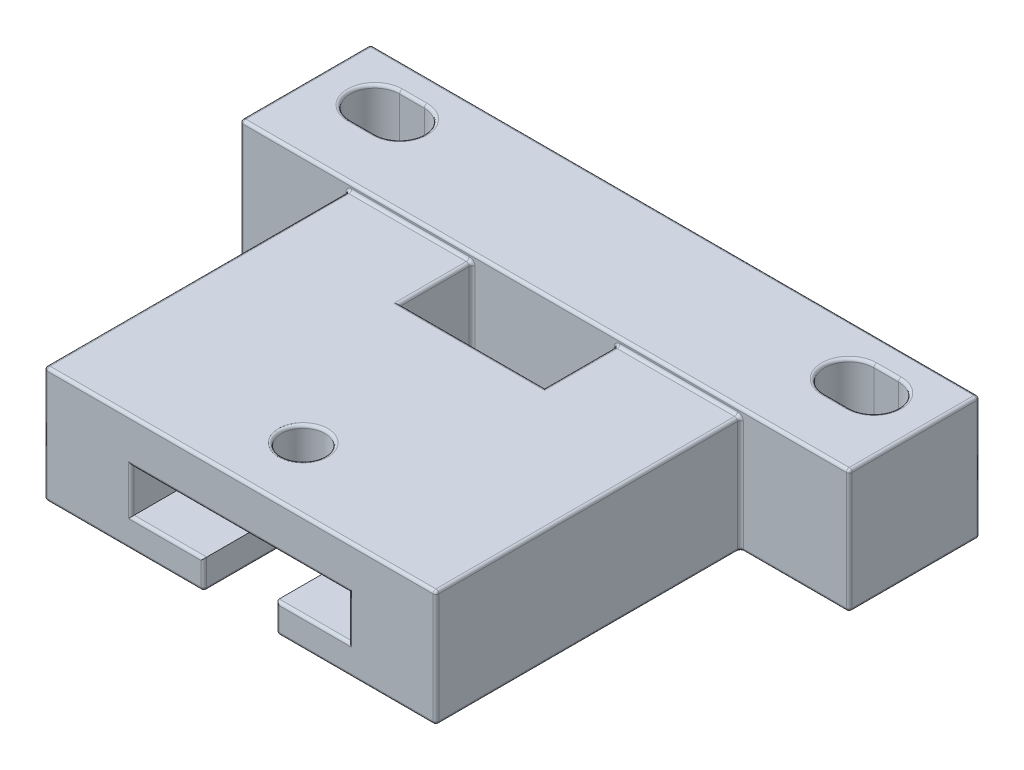
SolidWorks part; units mm, degrees
ref_plane "Front Plane" through (0, 0, 0) normal (0, 0, 1) x (1, 0, 0)
ref_plane "Top Plane" through (0, 0, 0) normal (0, 1, 0) x (1, 0, 0)
ref_plane "Right Plane" through (0, 0, 0) normal (1, 0, 0) x (0, 0, -1)
sketch "Sketch2" plane through (0, 0, 0) normal (0, 1, 0) x (1, 0, 0)
  line L0 (-17.2, 1) -> (-15.5, 1) construction
  line L1 (21, -4.5) -> (-21, -4.5)
  line L2 (21, -4.5) -> (21, 4.5)
  line L3 (21, 4.5) -> (-21, 4.5)
  line L4 (-21, -4.5) -> (-21, 4.5)
  line L5 (-17.2, 2.7) -> (-15.5, 2.7)
  line L6 (-17.2, -0.7) -> (-15.5, -0.7)
  line L9 (-21, 4.5) -> (21, -4.5) construction
  line L10 (-21, -4.5) -> (21, 4.5) construction
  line L13 (0, 0) -> (0, 3.9159)
  line L14 (17.2, 1) -> (15.5, 1) construction
  line L15 (17.2, 2.7) -> (15.5, 2.7)
  line L16 (17.2, -0.7) -> (15.5, -0.7)
  arc A4 (-17.2, 2.7) -> (-17.2, -0.7) centre (-17.2, 1) ccw
  arc A5 (-15.5, -0.7) -> (-15.5, 2.7) centre (-15.5, 1) ccw
  arc A6 (17.2, 2.7) -> (17.2, -0.7) centre (17.2, 1) cw
  arc A7 (15.5, -0.7) -> (15.5, 2.7) centre (15.5, 1) cw
  point P0 (0, 0)
  point P5 (-16.35, 1)
  point P13 (-18.9, 1)
  point P14 (0, 0)
  point P19 (16.35, 1)
  dimension "D6" = 2.1
  dimension "D1" = 42
  dimension "D2" = 9
  dimension "D3" = 1.7
  dimension "D4" = 3.4
  dimension "D5" = 3.8
extrude "Boss-Extrude1" add sketch "Sketch2" along normal blind 8.5
sketch "Sketch3" plane through (0, 0, 4.5) normal (0, 0, 1) x (1, 0, 0)
  line L0 (-13.5, 0) -> (13.5, 0)
  line L1 (21, 0) -> (-21, 0) construction
  line L2 (-13.5, 0) -> (-13.5, 8)
  line L3 (-13.5, 8) -> (13.5, 8)
  line L4 (13.5, 8) -> (13.5, 0)
  point P6 (0, 0)
  dimension "D1" = 27
  dimension "D2" = 8
extrude "Boss-Extrude2" add sketch "Sketch3" along normal blind 21
sketch "Sketch4" plane through (0, 8, 0) normal (0, 1, 0) x (1, 0, 0)
  line L0 (5, -4.5) -> (-5, -4.5)
  line L2 (13.5, -4.5) -> (-13.5, -4.5) construction
  line L3 (-5, -4.5) -> (-5, -9.5)
  line L4 (-5, -9.5) -> (5, -9.5)
  line L5 (5, -9.5) -> (5, -4.5)
  point P3 (0, -4.5)
  dimension "D1" = 10
  dimension "D3" = 5
extrude "Cut-Extrude1" cut sketch "Sketch4" against normal blind 21
sketch "Sketch8" plane through (0, 0, 25.5) normal (0, 0, 1) x (1, 0, 0)
  line L0 (2.5, 0) -> (-2.5, 0)
  line L1 (-13.5, 0) -> (13.5, 0) construction
  line L2 (-2.5, 0) -> (-2.5, 2)
  line L3 (-2.5, 2) -> (-7.5, 2)
  line L4 (-7.5, 2) -> (-7.5, 5.0121)
  line L5 (-7.5, 5.0121) -> (7.5, 5.0121)
  line L6 (7.5, 5.0121) -> (7.5, 2)
  line L7 (7.5, 2) -> (2.5, 2)
  line L8 (2.5, 2) -> (2.5, 0)
  point P6 (0, 0)
  dimension "D1" = 5
  dimension "D2" = 2
  dimension "D3" = 5
  dimension "D4" = 5
  dimension "D5" = 15
  dimension "D6" = 3.0121
extrude "Cut-Extrude3" cut sketch "Sketch8" against normal blind 10
sketch "Sketch9" plane through (0, 8, 0) normal (0, 1, 0) x (1, 0, 0)
  circle A0 centre (0, -21.1478) radius 1.5
  dimension "D1" = 3
extrude "Cut-Extrude4" cut sketch "Sketch9" against normal blind 10
fillet "Fillet1" radius 0.2 69 edges at (5, 4, 4.5) (13.5, 4, 4.5) (-13.5, 4, 4.5) (-5, 4, 4.5) (-21, 4.25, 4.5) (21, 4.25, 4.5) (21, 4.25, -4.5) (-21, 4.25, -4.5) (18.9, 8.5, -1) (16.35, 8.5, -2.7) (13.8, 8.5, -1) (16.35, 8.5, 0.7) (0, 8.5, -4.5) (21, 8.5, 0) (0, 8.5, 4.5) (-21, 8.5, 0) (-16.35, 8.5, -2.7) (-18.9, 8.5, -1) (-16.35, 8.5, 0.7) (-13.8, 8.5, -1) (-7.5, 3.5061, 15.5) (0, 5.0121, 15.5) (7.5, 3.5061, 15.5) (5, 2, 15.5) (2.5, 1, 15.5) (-2.5, 1, 15.5) (-5, 2, 15.5) (13.8, 0, -1) (16.35, 0, -2.7) (18.9, 0, -1) (16.35, 0, 0.7) (-16.35, 0, 0.7) (-18.9, 0, -1) (-16.35, 0, -2.7) (-13.8, 0, -1) (5, 0, 7) (0, 0, 9.5) (-5, 0, 7) (0, 0, 4.5) (13.5, 0, 15) (17.25, 0, 4.5) (21, 0, 0) (0, 0, -4.5) (-21, 0, 0) (-17.25, 0, 4.5) (-13.5, 0, 15) (-2.5, 0, 20.5) (0, 0, 15.5) (2.5, 0, 20.5) (5, 2, 25.5) (7.5, 3.5061, 25.5) (0, 5.0121, 25.5) (-7.5, 3.5061, 25.5) (-5, 2, 25.5) (-2.5, 1, 25.5) (-8, 0, 25.5) (-13.5, 4, 25.5) (13.5, 4, 25.5) (8, 0, 25.5) (2.5, 1, 25.5) (5, 8, 7) (9.25, 8, 4.5) (13.5, 8, 15) (0, 8, 25.5) (-13.5, 8, 15) (-9.25, 8, 4.5) (-5, 8, 7) (0, 8, 9.5) (-1.5, 8, 21.1478)
equation "\"5nn\"=4.94691"
